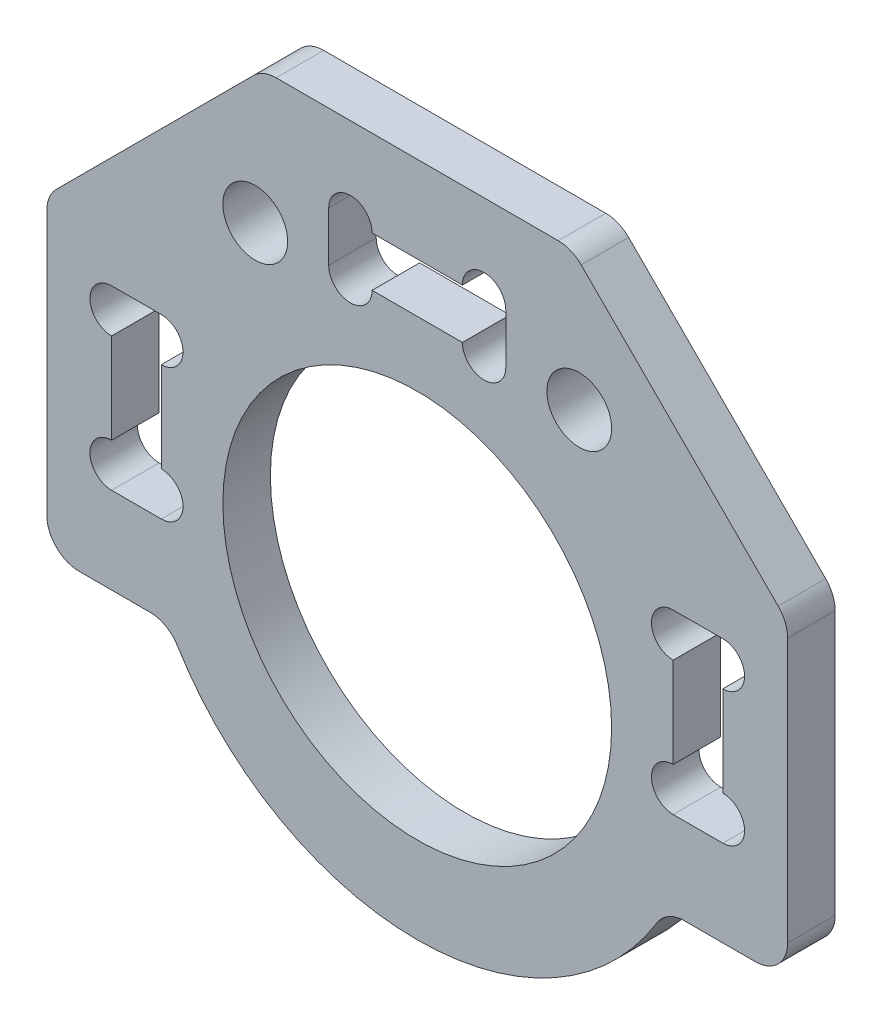
SolidWorks part; units mm, degrees
material "Thornel Mat VMA"
ref_plane "前视基准面" through (0, 0, 0) normal (0, 0, 1) x (1, 0, 0)
ref_plane "上视基准面" through (0, 0, 0) normal (0, 1, 0) x (1, 0, 0)
ref_plane "右视基准面" through (0, 0, 0) normal (1, 0, 0) x (0, 0, -1)
sketch "草图1" plane through (0, 0, 0) normal (0, 0, 1) x (1, 0, 0)
  line L0 (0, 0) -> (0, -6.2772) construction
  line L1 (4.1, -1.15) -> (-4.1, -1.15)
  line L2 (4.1, -1.15) -> (4.1, 1.15)
  line L3 (4.1, 1.15) -> (-4.1, 1.15)
  line L4 (-4.1, -1.15) -> (-4.1, 1.15)
  line L5 (4.1, -1.15) -> (-4.1, 1.15) construction
  line L6 (4.1, 1.15) -> (-4.1, -1.15) construction
  line L7 (-11.85, -15.2) -> (-14.15, -15.2)
  line L8 (-11.85, -15.2) -> (-11.85, -7)
  line L9 (-11.85, -7) -> (-14.15, -7)
  line L10 (-14.15, -15.2) -> (-14.15, -7)
  line L11 (-11.85, -15.2) -> (-14.15, -7) construction
  line L12 (-11.85, -7) -> (-14.15, -15.2) construction
  line L13 (11.85, -7) -> (14.15, -7)
  line L14 (14.15, -15.2) -> (14.15, -7)
  line L15 (11.85, -15.2) -> (14.15, -15.2)
  line L16 (11.85, -15.2) -> (11.85, -7)
  line L17 (13, -7) -> (13, -9.0659) construction
  line L18 (-11.5064, -19.2) -> (-17.15, -19.2)
  line L19 (-17.15, -19.2) -> (-17.15, 5.15)
  line L20 (11.5064, -19.2) -> (17.15, -19.2)
  line L21 (17.15, -19.2) -> (17.15, 5.15)
  line L22 (-17.15, 5.15) -> (17.15, 5.15)
  circle A0 centre (0, -13.15) radius 9
  arc A1 (-11.5064, -19.2) -> (11.5064, -19.2) centre (0, -13.15) ccw
  circle A3 centre (-14.15, -14.195) radius 1.005
  circle A4 centre (-11.85, -14.195) radius 1.005
  circle A5 centre (-11.85, -8.005) radius 1.005
  circle A6 centre (-14.15, -8.005) radius 1.005
  circle A7 centre (14.15, -14.195) radius 1.005
  circle A8 centre (11.85, -14.195) radius 1.005
  circle A9 centre (11.85, -8.005) radius 1.005
  circle A10 centre (14.15, -8.005) radius 1.005
  circle A11 centre (-3.095, 1.15) radius 1.005
  circle A12 centre (3.095, 1.15) radius 1.005
  circle A13 centre (3.095, -1.15) radius 1.005
  circle A14 centre (-3.095, -1.15) radius 1.005
  circle A15 centre (-7.5, -1.15) radius 1.5
  circle A16 centre (7.5, -1.15) radius 1.5
  point P0 (0, 0)
  point P6 (-13, -11.1)
  dimension "D6" = 18
  dimension "D8" = 2.01
  dimension "D11" = 4
  dimension "D13" = 3
  dimension "D1" = 26
  dimension "D2" = 2.3
  dimension "D3" = 2.3
  dimension "D4" = 8.2
  dimension "D5" = 11.1
  dimension "D7" = 12
  dimension "D9" = 3
  dimension "D10" = 4
  dimension "D12" = 4
  dimension "D14" = 15
extrude "凸台-拉伸1" add sketch "草图1" along normal blind 2.2 contours L18 A1 L20 L21 L22 L19 A14 L4 A11 L3 A12 L2 A13 L1 A6 L9 A5 L8 A4 L7 A3 L10 A0 L13 A10 L14 A7 L15 A8 L16 A9
chamfer "倒角1" distance 10 angle 45 2 edges at (17.15, 5.15, 1.1) (-17.15, 5.15, 1.1)
fillet "圆角1" radius 1.5 8 edges at (17.15, -19.2, 1.1) (11.5064, -19.2, 1.1) (-11.5064, -19.2, 1.1) (-17.15, -19.2, 1.1) (-7.15, 5.15, 1.1) (7.15, 5.15, 1.1) (17.15, -4.85, 1.1) (-17.15, -4.85, 1.1)
